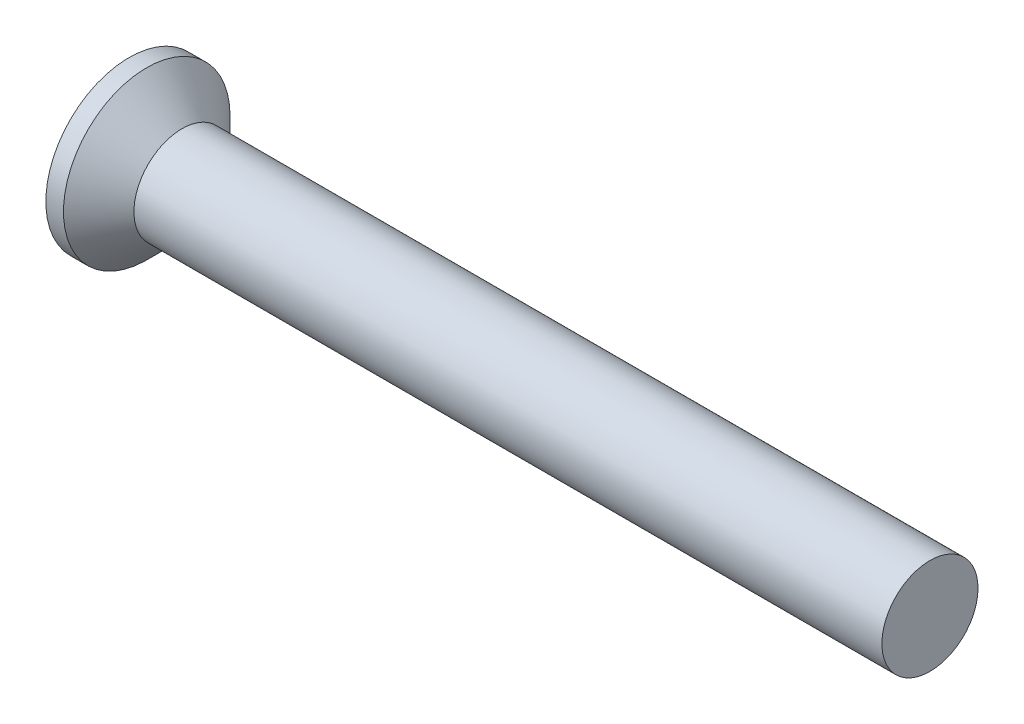
SolidWorks part; units mm, degrees
ref_plane "Front" through (0, 0, 0) normal (0, 0, 1) x (1, 0, 0)
ref_plane "Top" through (0, 0, 0) normal (0, 1, 0) x (1, 0, 0)
ref_plane "Right" through (0, 0, 0) normal (1, 0, 0) x (0, 0, -1)
sketch "Sketch1" plane through (0, 0, 0) normal (0, 0, 1) x (1, 0, 0)
  line L0 (25, 1.5) -> (2.65, 1.5)
  line L1 (2.65, 1.5) -> (1.65, 1.5)
  line L2 (1.65, 1.5) -> (0.55, 2.6)
  line L3 (0.55, 2.6) -> (0, 2.6)
  line L4 (25, 1.5) -> (25, 0)
  line L5 (4.5158, 0) -> (-89.8219, 0) construction
  line L6 (25, 0) -> (0, 0)
  line L7 (0, 2.6) -> (0, 0)
  dimension "D1" = 45
  dimension "dk" = 5.2
  dimension "l" = 25
  dimension "k" = 1.65
  dimension "a" = 1
  dimension "d" = 3
revolve "Base" add sketch "Sketch1" angle 360 about L5
cosmetic thread "ThreadCosmetic1" parameters "bb"=23.35
sketch "Sketch6" plane through (0, 0, 0) normal (1, 0, 0) x (0, 0, -1)
  line L0 (-1.9271, 0) -> (2.0512, 0) construction
  line L1 (0, 1.8651) -> (0, -2.0207) construction
  line L2 (0.32, 0.32) -> (0.32, 1.6)
  line L3 (0.32, 1.6) -> (-0.32, 1.6)
  line L4 (-0.32, 0.32) -> (-0.32, 1.6)
  line L5 (0.32, 0.32) -> (1.6, 0.32)
  line L6 (1.6, 0.32) -> (1.6, -0.32)
  line L7 (-1.6, 0.32) -> (-1.6, -0.32)
  line L8 (-0.32, 0.32) -> (-1.6, 0.32)
  line L9 (-0.32, -0.32) -> (-1.6, -0.32)
  line L10 (0.32, -0.32) -> (1.6, -0.32)
  line L11 (-0.32, -0.32) -> (-0.32, -1.6)
  line L12 (0.32, -1.6) -> (-0.32, -1.6)
  line L13 (0.32, -0.32) -> (0.32, -1.6)
  point P16 (-1.6, 0)
  point P17 (1.6, 0)
extrude "CrossRecess" cut sketch "Sketch6" along normal blind 0.825
draft "Draft9" type of draft neutral plane draft angle 30 faces to draft 4 face at (0.4125, -1.6, 0) face at (0.4125, 0, 1.6) face at (0.4125, 0, -1.6) face at (0.4125, 1.6, 0) neutral plane through (0, 2.6, 0) neutral plane normal (-1, 0, 0) parameters "D1"=30
fillet "Fillet5" radius 0.3 4 edges at (0.4125, -0.32, -0.32) (0.4125, -0.32, 0.32) (0.4125, 0.32, -0.32) (0.4125, 0.32, 0.32)
sketch "Sketch7" plane through (0, 0, 0) normal (1, 0, 0) x (0, 0, -1)
  line L0 (-2.0126, 0) -> (1.9757, 0) construction
  line L1 (0, 1.9314) -> (0, -2.0126) construction
  line L2 (0, 0) -> (1.5555, 1.5555) construction
  line L3 (0, 0.4782) -> (1.1314, 1.1314)
  line L4 (-1.5402, 1.5402) -> (0, 0) construction
  line L5 (0.4782, 0) -> (1.1314, 1.1314)
  line L6 (0, -0.4782) -> (1.1314, -1.1314)
  line L7 (0.4782, 0) -> (1.1314, -1.1314)
  line L8 (-0.4782, 0) -> (-1.1314, -1.1314)
  line L9 (0, -0.4782) -> (-1.1314, -1.1314)
  line L10 (-0.4782, 0) -> (-1.1314, 1.1314)
  line L11 (0, 0.4782) -> (-1.1314, 1.1314)
  dimension "D3" = 15
  dimension "m" = 3.2
extrude "Cut-Extrude3" [suppressed] cut sketch "Sketch7" along normal blind 10 draft 20
sketch "Sketch10" plane through (0, 0, 0) normal (0, 0, 1) x (1, 0, 0)
  line L0 (62.2289, 0) -> (-1.9277, 0) construction
  line L1 (1.65, 1.5) -> (2.15, 1.5)
  line L4 (2.15, 1.5) -> (2.15, 0)
  line L7 (2.15, 0) -> (1.65, 0)
  line L9 (1.65, 1.5) -> (0.55, 2.6) construction
  line L10 (1.65, 1.5) -> (1.65, 0)
  dimension "p" = 0.5
revolve "Revolve2" add sketch "Sketch10" angle 360 about L0
sketch "Sketch8" plane through (0, 0, 0) normal (0, 0, 1) x (1, 0, 0)
  line L0 (0, 1.5) -> (-1.25, 1.2295)
  line L1 (-1.25, 1.2295) -> (5, 1.2295)
  line L3 (25, -1.5) -> (25, 1.5) construction
  line L6 (5, 1.2295) -> (5, 6.2295)
  line L7 (5, 6.2295) -> (0, 6.2295)
  line L8 (0, 6.2295) -> (0, 1.5)
  line L9 (62.4753, 0) -> (52.9594, 0) construction
  dimension "D1" = 5
  dimension "x" = 1.25
  dimension "d" = 3
  dimension "THD_MINOR" = 2.459
  dimension "b" = 25
sketch "Sketch11" plane through (0, 0, 0) normal (0, 0, 1) x (1, 0, 0)
  line L0 (25, 1.2657) -> (25.1353, 1.5)
  line L1 (25.1353, 1.5) -> (25.1353, 1.7705)
  line L2 (25.1353, 1.7705) -> (24.8648, 1.7705)
  line L3 (24.8648, 1.7705) -> (24.8648, 1.5)
  line L4 (24.8648, 1.5) -> (25, 1.2657)
  line L5 (25, -1.5) -> (25, 1.5) construction
  line L6 (0, 0) -> (66.0064, 0) construction
  dimension "D1" = 3
  dimension "D2" = 0.2705
revolve "Cut-Revolve10" [suppressed] cut sketch "Sketch11" angle 360 about L6
pattern_linear "LPattern10" [suppressed] count 72 spacing 0.3246 along (1, 0, 0)
equation "\"D1@Sketch6\" = \"m@Sketch6\" / 5"
equation "\"D1@CrossRecess\" = \"k@Sketch1\" / 2"
equation "\"D1@Sketch11\" = \"d@Sketch1\""
equation "\"D2@Sketch11\" =  ( \"d@Sketch1\" - \"THD_MINOR@ThreadCosmetic1\" )  / 2"
equation "\"D3@LPattern10\" = \"D2@Sketch11\" * 1.2"
equation "\"D1@LPattern10\" = \"bb@ThreadCosmetic1\" / \"D3@LPattern10\" "
